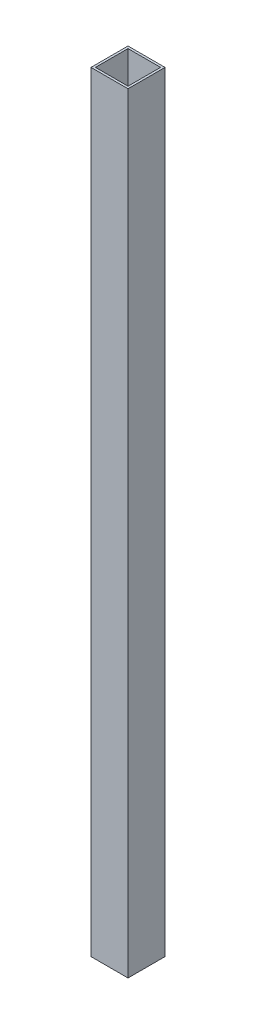
SolidWorks part; units mm, degrees
ref_plane "Front Plane" through (0, 0, 0) normal (0, 0, 1) x (1, 0, 0)
ref_plane "Top Plane" through (0, 0, 0) normal (0, 1, 0) x (1, 0, 0)
ref_plane "Right Plane" through (0, 0, 0) normal (1, 0, 0) x (0, 0, -1)
sketch "Sketch1" plane through (0, 0, 0) normal (0, 1, 0) x (1, 0, 0)
  line L0 (-26.6278, 1.8372) -> (-14.1278, -10.6628) construction
  line L1 (-26.6278, 1.8372) -> (-14.1278, 1.8372)
  line L2 (-26.6278, 1.8372) -> (-26.6278, -10.6628)
  line L3 (-26.6278, -10.6628) -> (-14.1278, -10.6628)
  line L4 (-14.1278, 1.8372) -> (-14.1278, -10.6628)
  line L5 (-26.6278, -10.6628) -> (-14.1278, 1.8372) construction
  line L7 (-25.8778, 1.0872) -> (-14.8778, 1.0872)
  line L8 (-25.8778, 1.0872) -> (-25.8778, -9.9128)
  line L9 (-25.8778, -9.9128) -> (-14.8778, -9.9128)
  line L10 (-14.8778, 1.0872) -> (-14.8778, -9.9128)
  line L11 (-25.8778, 1.0872) -> (-14.8778, -9.9128) construction
  line L12 (-25.8778, -9.9128) -> (-14.8778, 1.0872) construction
  point P4 (-20.3778, -4.4128)
extrude "Boss-Extrude3" add sketch "Sketch1" along normal blind 260
